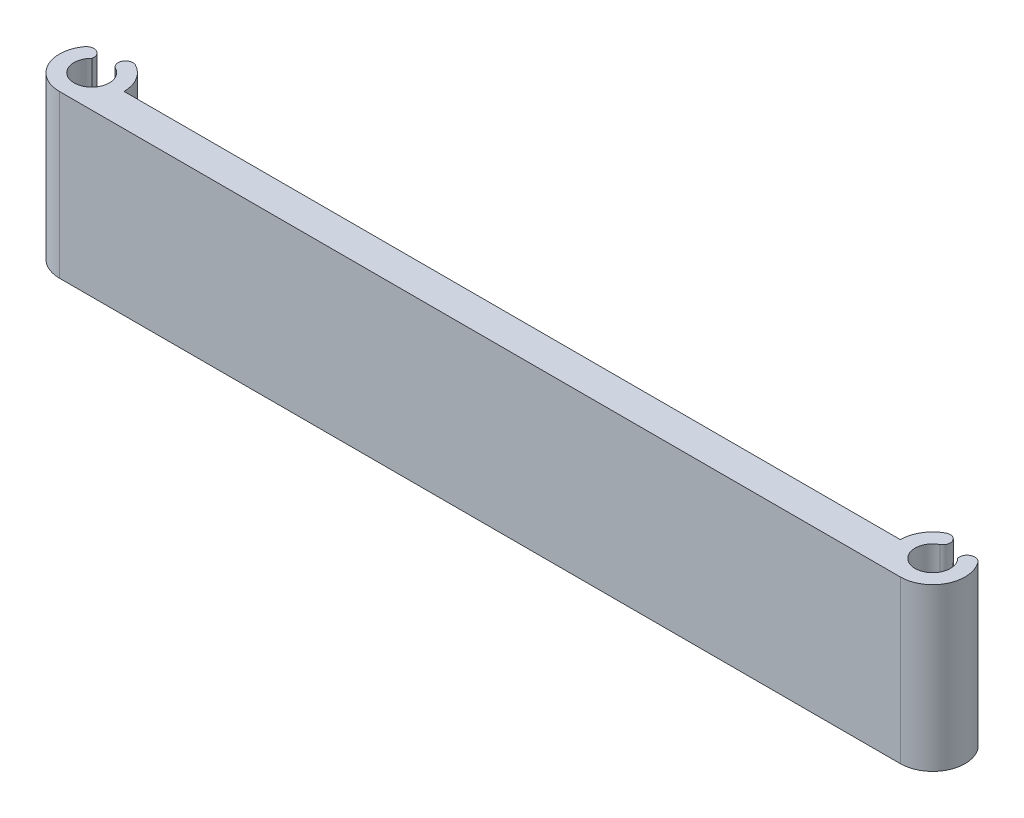
SolidWorks part; units mm, degrees
ref_plane "Plano frontal" through (0, 0, 0) normal (0, 0, 1) x (1, 0, 0)
ref_plane "Plano superior" through (0, 0, 0) normal (0, 1, 0) x (1, 0, 0)
ref_plane "Plano direito" through (0, 0, 0) normal (1, 0, 0) x (0, 0, -1)
sketch "Esboço1" plane through (0, 0, 0) normal (0, 1, 0) x (1, 0, 0)
  line L0 (-72, 0) -> (72, 0)
  line L2 (78, -6) -> (-78, -6)
  line L3 (0, 0) -> (0, -6) construction
  arc A0 (-80.2962, 2.3351) -> (-76.4496, 2.8847) centre (-78, 0) ccw
  arc A1 (-72, 0) -> (-75.1595, 5.285) centre (-78, 0) ccw
  arc A2 (-82.8639, 3.5132) -> (-78, -6) centre (-78, 0) ccw
  arc A3 (-80.2962, 2.3351) -> (-82.8639, 3.5132) centre (-81.6966, 2.6701) ccw
  arc A4 (-76.4496, 2.8847) -> (-75.1595, 5.285) centre (-75.8045, 4.0849) cw
  arc A5 (76.4496, 2.8847) -> (75.1595, 5.285) centre (75.8045, 4.0849) ccw
  arc A6 (80.2962, 2.3351) -> (82.8639, 3.5132) centre (81.6966, 2.6701) cw
  arc A7 (82.8639, 3.5132) -> (78, -6) centre (78, 0) cw
  arc A8 (72, 0) -> (75.1595, 5.285) centre (78, 0) cw
  arc A9 (80.2962, 2.3351) -> (76.4496, 2.8847) centre (78, 0) cw
  dimension "D1" = 6.55
  dimension "D2" = 12
  dimension "D4" = 3.8467
  dimension "D3" = 78
  dimension "D5" = 2.825
  dimension "D6" = 2.4003
extrude "Ressalto-extrusão1" add sketch "Esboço1" along normal blind 30
